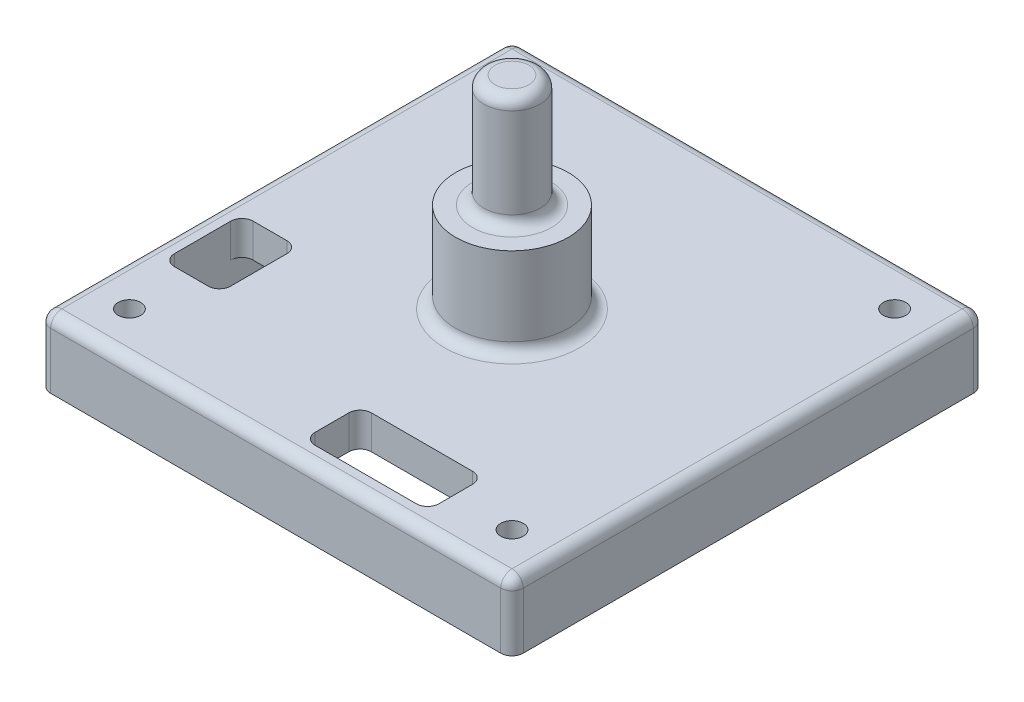
SolidWorks part; units mm, degrees
ref_plane "Front" through (0, 0, 0) normal (0, 0, 1) x (1, 0, 0)
ref_plane "Top" through (0, 0, 0) normal (0, 1, 0) x (1, 0, 0)
ref_plane "Right" through (0, 0, 0) normal (1, 0, 0) x (0, 0, -1)
sketch "Sketch1" plane through (0, 0, 0) normal (0, 1, 0) x (1, 0, 0)
  line L1 (-21, 21) -> (21, 21)
  line L2 (-21, 21) -> (-21, -21)
  line L3 (-21, -21) -> (21, -21)
  line L4 (21, 21) -> (21, -21)
  line L5 (-21, 21) -> (21, -21) construction
  line L6 (-21, -21) -> (21, 21) construction
  point P0 (0, 0)
  dimension "D1" = 42
extrude "Boss-Extrude1" add sketch "Sketch1" along normal blind 6
sketch "Sketch2" plane through (0, 0, 0) normal (0, -1, 0) x (1, 0, 0)
  line L1 (-19.25, 19.25) -> (19.25, 19.25)
  line L2 (-19.25, 19.25) -> (-19.25, -19.25)
  line L3 (-19.25, -19.25) -> (19.25, -19.25)
  line L4 (19.25, 19.25) -> (19.25, -19.25)
  line L5 (-19.25, 19.25) -> (19.25, -19.25) construction
  line L6 (-19.25, -19.25) -> (19.25, 19.25) construction
  point P0 (0, 0)
  dimension "D1" = 38.5
extrude "Cut-Extrude1" cut sketch "Sketch2" against normal blind 3
sketch "Sketch3" plane through (0, 3, 0) normal (0, -1, 0) x (1, 0, 0)
  line L0 (19.25, 19.25) -> (-19.25, 19.25) construction
  line L1 (-19.25, 11.75) -> (-14.25, 11.75)
  line L2 (-19.25, 11.75) -> (-19.25, 4.75)
  line L3 (-19.25, 4.75) -> (-14.25, 4.75)
  line L4 (-14.25, 11.75) -> (-14.25, 4.75)
  line L5 (-19.25, 11.75) -> (-14.25, 4.75) construction
  line L6 (-19.25, 4.75) -> (-14.25, 11.75) construction
  line L7 (0.75, 19.25) -> (11.75, 19.25)
  line L8 (0.75, 19.25) -> (0.75, 14.25)
  line L9 (0.75, 14.25) -> (11.75, 14.25)
  line L10 (11.75, 19.25) -> (11.75, 14.25)
  line L11 (0.75, 19.25) -> (11.75, 14.25) construction
  line L12 (0.75, 14.25) -> (11.75, 19.25) construction
  line L13 (-19.25, 19.25) -> (-19.25, -19.25) construction
  line L14 (19.25, 19.25) -> (-19.25, 19.25) construction
  line L15 (19.25, -19.25) -> (19.25, 19.25) construction
  point P0 (-16.75, 8.25)
  point P5 (6.25, 16.75)
  dimension "D1" = 7.5
  dimension "D2" = 7
  dimension "D3" = 5
  dimension "D4" = 5
  dimension "D5" = 7.5
  dimension "D6" = 11
extrude "Cut-Extrude2" cut sketch "Sketch3" against normal up to next
sketch "Sketch4" plane through (0, 3, 0) normal (0, -1, 0) x (1, 0, 0)
  line L0 (-19.25, 15.9103) -> (-19.25, 19.25)
  line L1 (17, -17) -> (-17, -17) construction
  line L2 (17, -17) -> (17, 17) construction
  line L3 (17, 17) -> (-17, 17) construction
  line L4 (-17, -17) -> (-17, 17) construction
  line L5 (17, -17) -> (-17, 17) construction
  line L6 (17, 17) -> (-17, -17) construction
  line L7 (-19.25, 19.25) -> (-19.25, -19.25) construction
  line L8 (-19.25, 19.25) -> (-15.9103, 19.25)
  line L9 (0.75, 19.25) -> (-19.25, 19.25) construction
  line L10 (0, 35.0408) -> (0, -41.1433) construction
  line L11 (-36.6087, 0) -> (46.6213, 0) construction
  line L12 (19.25, 19.25) -> (15.9103, 19.25)
  line L13 (19.25, 15.9103) -> (19.25, 19.25)
  line L14 (-19.25, -19.25) -> (-15.9103, -19.25)
  line L15 (-19.25, -15.9103) -> (-19.25, -19.25)
  line L16 (19.25, -15.9103) -> (19.25, -19.25)
  line L17 (19.25, -19.25) -> (15.9103, -19.25)
  arc A0 (-19.25, 15.9103) -> (-15.9103, 19.25) centre (-17, 17) ccw
  arc A1 (19.25, 15.9103) -> (15.9103, 19.25) centre (17, 17) cw
  arc A2 (-19.25, -15.9103) -> (-15.9103, -19.25) centre (-17, -17) cw
  arc A3 (19.25, -15.9103) -> (15.9103, -19.25) centre (17, -17) ccw
  point P0 (0, 0)
  dimension "D1" = 34
  dimension "D2" = 5
extrude "Boss-Extrude2" add sketch "Sketch4" along normal blind 1.5
sketch "Sketch5" plane through (0, 1.5, 0) normal (0, -1, 0) x (1, 0, 0)
  circle A0 centre (-17, 17) radius 1
  circle A1 centre (17, 17) radius 1
  circle A2 centre (17, -17) radius 1
  circle A3 centre (-17, -17) radius 1
  dimension "D1" = 2
extrude "Cut-Extrude3" cut sketch "Sketch5" against normal through all
sketch "Sketch6" plane through (0, 6, 0) normal (0, 1, 0) x (1, 0, 0)
  circle A0 centre (0, 0) radius 5
  dimension "D1" = 10
extrude "Boss-Extrude3" add sketch "Sketch6" along normal blind 8
sketch "Sketch7" plane through (0, 14, 0) normal (0, 1, 0) x (1, 0, 0)
  circle A0 centre (0, 0) radius 2.5
  dimension "D1" = 5
extrude "Boss-Extrude4" add sketch "Sketch7" along normal blind 10
fillet "Fillet1" radius 1 19 edges at (0, 24, 2.5) (0, 6, -21) (-21, 6, 0) (0, 6, 21) (21, 6, 0) (-21, 3, 21) (-21, 3, -21) (21, 3, -21) (21, 3, 21) (0.75, 4.5, 14.25) (0.75, 4.5, 19.25) (11.75, 4.5, 19.25) (11.75, 4.5, 14.25) (-19.25, 4.5, 4.75) (-19.25, 4.5, 11.75) (-14.25, 4.5, 11.75) (-14.25, 4.5, 4.75) (0, 14, 2.5) (0, 6, 5)
